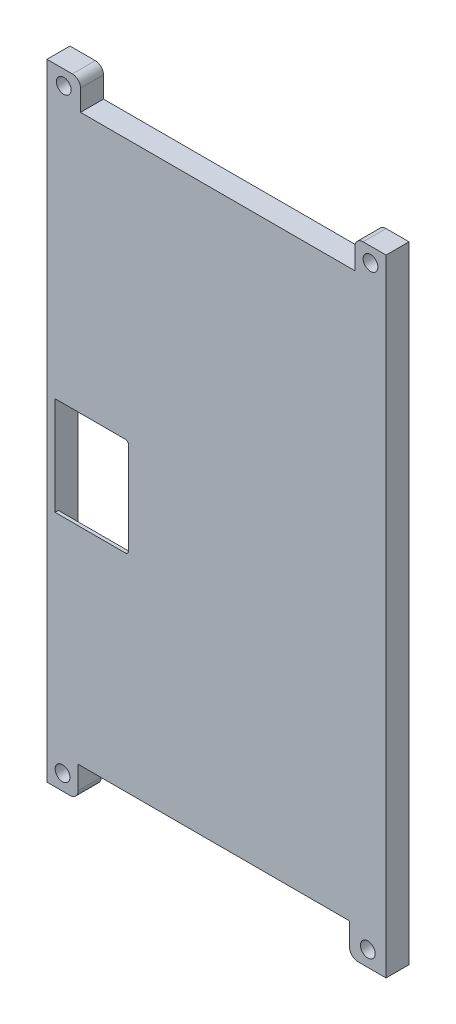
SolidWorks part; units mm, degrees
ref_plane "Ön Düzlem" through (0, 0, 0) normal (1, 0, 0) x (0, 1, 0)
ref_plane "Üst Düzlem" through (0, 0, 0) normal (0, 0, 1) x (0, 1, 0)
ref_plane "Sağ Düzlem" through (0, 0, 0) normal (0, 1, 0) x (-1, 0, 0)
sketch "Çizim1" plane through (0, 0, 0) normal (0, 0, 1) x (0, 1, 0)
  line L0 (-35.9386, 27.9204) -> (129.0614, 27.9204)
  line L1 (-35.9386, 27.9204) -> (-35.9386, -70.4796)
  line L2 (-35.9386, -70.4796) -> (129.0614, -70.4796)
  line L3 (129.0614, -70.4796) -> (129.0614, 27.9204)
  line L5 (134.0614, 27.9204) -> (134.0614, 30.4204) construction
  line L6 (-38.4386, 30.4204) -> (134.0614, 30.4204) construction
  line L7 (134.0614, 30.4204) -> (134.0614, -72.9796) construction
  line L9 (-38.4386, -72.9796) -> (134.0614, -72.9796) construction
  line L11 (-38.4386, -72.9796) -> (-38.4386, 30.4204) construction
  line L12 (-38.4386, 30.4204) -> (-38.4386, -72.9796)
  line L13 (-38.4386, -72.9796) -> (134.0614, -72.9796)
  line L14 (134.0614, -72.9796) -> (134.0614, 30.4204)
  line L15 (134.0614, 30.4204) -> (-38.4386, 30.4204)
  dimension "D1" = 129.0614
  dimension "D2" = 134.0614
  dimension "D3" = 35.9386
  dimension "D4" = 38.4386
  dimension "D5" = 27.9204
  dimension "D6" = 30.4204
  dimension "D7" = 70.4796
  dimension "D8" = 72.9796
extrude "Yükseklik-Ekstrüzyon1" add sketch "Çizim1" along normal blind 6
sketch "Çizim2" plane through (0, 0, 6) normal (0, 0, 1) x (1, 0, 0)
  line L0 (-30.4204, 54.5614) -> (-30.4204, 134.0614)
  line L1 (-30.4204, -38.4386) -> (72.9796, -38.4386)
  line L2 (-30.4204, -38.4386) -> (-30.4204, 24.5614)
  line L3 (-30.4204, 134.0614) -> (72.9796, 134.0614)
  line L4 (72.9796, -38.4386) -> (72.9796, 134.0614)
  line L5 (-27.9204, 129.0614) -> (-27.9204, -35.9386) construction
  line L6 (-27.9204, 24.5614) -> (-6.5204, 24.5614)
  line L7 (-5.5204, 25.5614) -> (-5.5204, 53.5614)
  line L8 (-6.5204, 54.5614) -> (-27.9204, 54.5614)
  line L9 (-27.9204, 24.5614) -> (-27.9204, 54.5614)
  line L12 (-30.4204, 54.5614) -> (-30.4204, 24.5614)
  arc A0 (-6.5204, 24.5614) -> (-5.5204, 25.5614) centre (-6.5204, 25.5614) ccw
  arc A1 (-5.5204, 53.5614) -> (-6.5204, 54.5614) centre (-6.5204, 53.5614) ccw
  dimension "D1" = 1
extrude "Yükseklik-Ekstrüzyon2" add sketch "Çizim2" along normal blind 1
sketch "Çizim3" plane through (0, 0, 0) normal (0, 0, 1) x (0, 1, 0)
  line L5 (-38.4386, 30.4204) -> (-47.9386, 30.4204)
  line L10 (-47.9386, 30.4204) -> (-47.9386, 23.4204)
  line L16 (-45.4386, 20.9204) -> (-38.4386, 20.9204)
  line L21 (-38.4386, 30.4204) -> (-38.4386, -72.9796) construction
  line L22 (-38.4386, 20.9204) -> (-38.4386, 30.4204)
  line L23 (-47.9386, 20.9204) -> (-38.4386, 30.4204) construction
  line L24 (-38.4386, -61.8538) -> (-45.4386, -61.8538)
  line L25 (-47.9386, -64.3538) -> (-47.9386, -72.9796)
  line L26 (-47.9386, -72.9796) -> (-38.4386, -72.9796)
  line L27 (-38.4386, -72.9796) -> (-38.4386, -61.8538)
  line L28 (-47.9386, -72.9796) -> (-38.4386, -61.8538) construction
  line L29 (142.9614, 30.4204) -> (134.0614, 30.4204)
  line L30 (134.0614, 30.4204) -> (134.0614, 20.1866)
  line L31 (134.0614, 20.1866) -> (140.4614, 20.1866)
  line L32 (142.9614, 22.6866) -> (142.9614, 30.4204)
  line L33 (134.0614, 20.1866) -> (142.9614, 30.4204) construction
  line L34 (140.4614, -63.4796) -> (134.0614, -63.4796)
  line L35 (134.0614, -63.4796) -> (134.0614, -72.9796)
  line L36 (134.0614, -72.9796) -> (142.9614, -72.9796)
  line L37 (142.9614, -72.9796) -> (142.9614, -65.9796)
  line L38 (134.0614, -72.9796) -> (142.9614, -63.4796) construction
  line L39 (134.0614, -72.9796) -> (134.0614, 30.4204) construction
  line L40 (134.0614, 30.4204) -> (-38.4386, 30.4204) construction
  line L41 (-38.4386, -72.9796) -> (134.0614, -72.9796) construction
  circle A4 centre (-43.1886, 25.6704) radius 2.25
  circle A5 centre (-43.1886, -67.4167) radius 2.25
  circle A6 centre (138.5114, 25.3035) radius 2.25
  circle A7 centre (138.5114, -68.2296) radius 2.25
  arc A8 (140.4614, 20.1866) -> (142.9614, 22.6866) centre (140.4614, 22.6866) ccw
  arc A9 (140.4614, -63.4796) -> (142.9614, -65.9796) centre (140.4614, -65.9796) cw
  arc A10 (-45.4386, -61.8538) -> (-47.9386, -64.3538) centre (-45.4386, -64.3538) ccw
  arc A11 (-47.9386, 23.4204) -> (-45.4386, 20.9204) centre (-45.4386, 23.4204) ccw
  dimension "D1" = 2.5
  dimension "D2" = 4.5
  dimension "D3" = 138.5114
  dimension "D4" = 43.1886
  dimension "D5" = 20.1866
  dimension "D6" = 61.8538
extrude "Yükseklik-Ekstrüzyon3" add sketch "Çizim3" along normal up to surface (7 mm away) up to face at (21.2796, 47.8114, 7)
